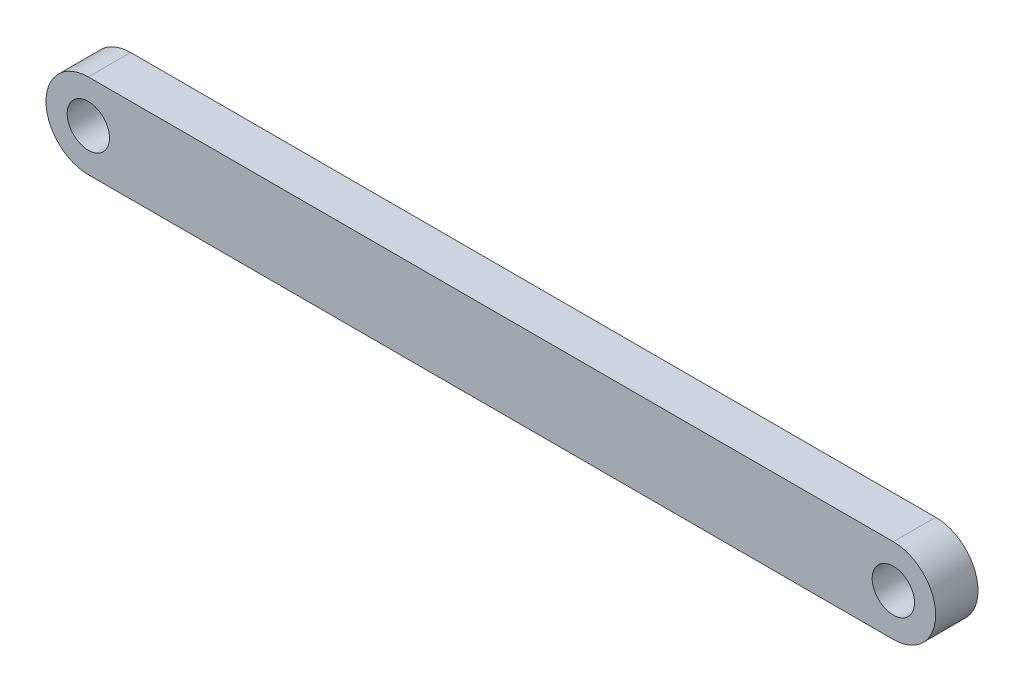
SolidWorks part; units mm, degrees
ref_plane "Plano frontal" through (0, 0, 0) normal (0, 0, 1) x (1, 0, 0)
ref_plane "Plano superior" through (0, 0, 0) normal (0, 1, 0) x (1, 0, 0)
ref_plane "Plano direito" through (0, 0, 0) normal (1, 0, 0) x (0, 0, -1)
sketch "Esboço1" plane through (0, 0, 0) normal (0, 0, 1) x (1, 0, 0)
  line L0 (-45.57, 20.9474) -> (49.49, 20.9474)
  line L1 (-45.57, 15.9474) -> (45.5778, 15.9474) construction
  line L2 (-45.57, 10.9474) -> (49.49, 10.9474)
  arc A0 (-45.57, 20.9474) -> (-45.57, 10.9474) centre (-45.57, 15.9474) ccw
  arc A1 (49.49, 20.9474) -> (49.49, 10.9474) centre (49.49, 15.9474) cw
  circle A2 centre (-45.57, 15.9474) radius 2.5
  circle A3 centre (49.49, 15.9474) radius 2.5
  point P3 (1.96, 20.9474)
  dimension "D1" = 95.06
  dimension "D2" = 5
extrude "Ressalto-extrusão1" add sketch "Esboço1" along normal blind 5
